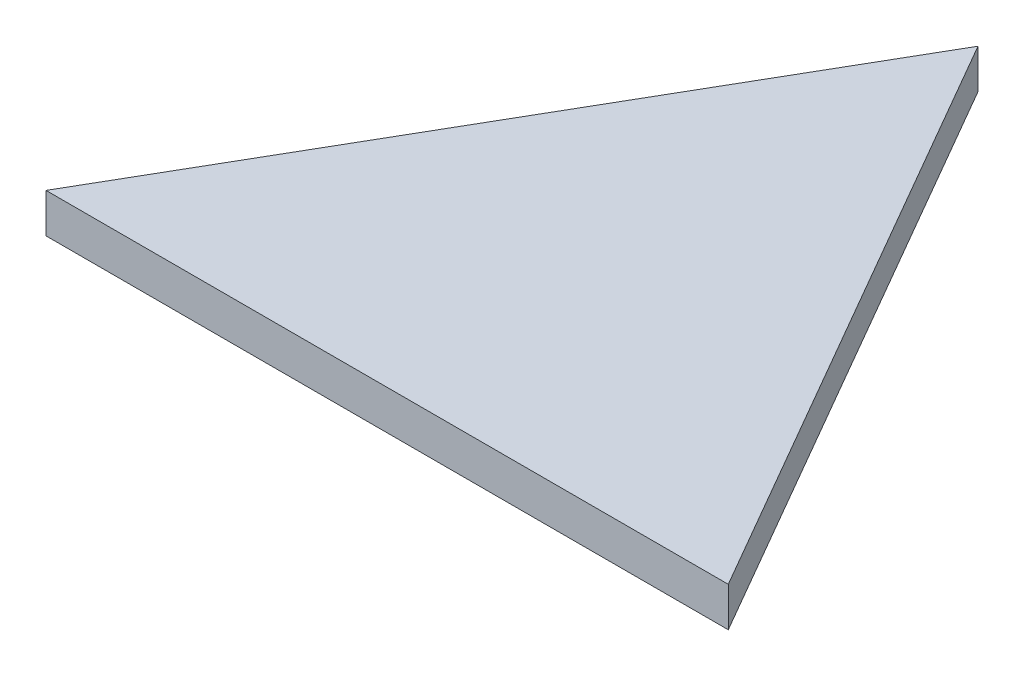
SolidWorks part; units mm, degrees
ref_plane "前视基准面" through (0, 0, 0) normal (0, 0, 1) x (1, 0, 0)
ref_plane "上视基准面" through (0, 0, 0) normal (0, 1, 0) x (1, 0, 0)
ref_plane "右视基准面" through (0, 0, 0) normal (1, 0, 0) x (0, 0, -1)
sketch "草图1" plane through (0, 0, 0) normal (0, 1, 0) x (1, 0, 0)
  line L1 (0, 100) -> (-86.6025, -50)
  line L2 (-86.6025, -50) -> (86.6025, -50)
  line L3 (86.6025, -50) -> (0, 100)
  circle A0 centre (0, 0) radius 50 construction
  dimension "D1" = 50
extrude "凸台-拉伸1" add sketch "草图1" along normal blind 10
